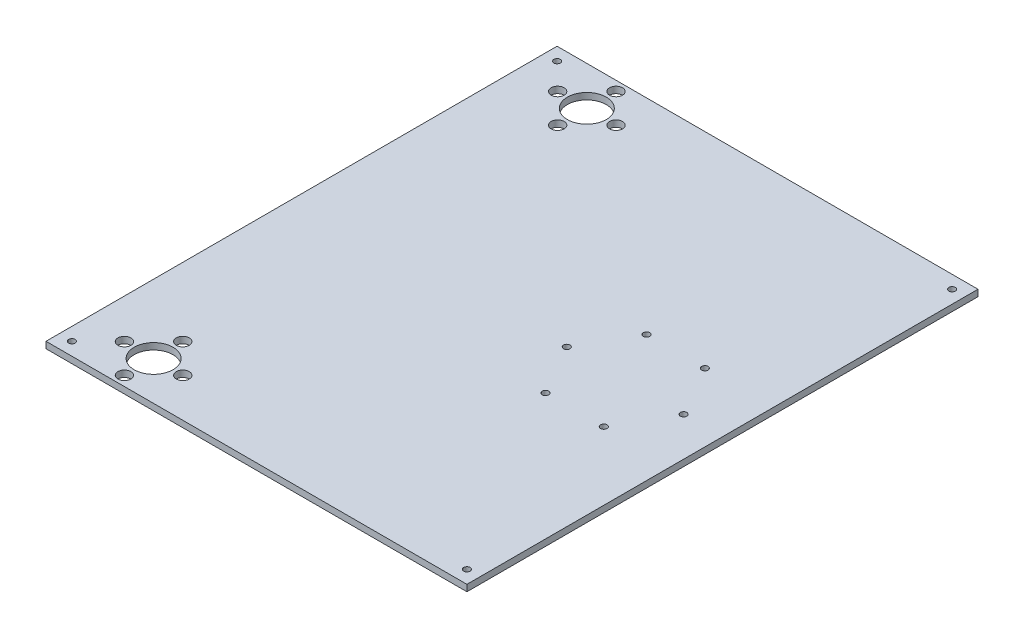
SolidWorks part; units mm, degrees
ref_plane "Front Plane" through (0, 0, 0) normal (0, 0, 1) x (1, 0, 0)
ref_plane "Top Plane" through (0, 0, 0) normal (0, 1, 0) x (1, 0, 0)
ref_plane "Right Plane" through (0, 0, 0) normal (1, 0, 0) x (0, 0, -1)
sketch "Sketch1" plane through (0, 0, 0) normal (0, 1, 0) x (1, 0, 0)
  line L1 (-162.25, 197) -> (162.25, 197)
  line L2 (-162.25, 197) -> (-162.25, -197)
  line L3 (-162.25, -197) -> (162.25, -197)
  line L4 (162.25, 197) -> (162.25, -197)
  line L5 (-162.25, 197) -> (162.25, -197) construction
  line L6 (-162.25, -197) -> (162.25, 197) construction
  point P0 (0, 0)
  dimension "D1" = 394
  dimension "D2" = 324.5
extrude "Boss-Extrude1" add sketch "Sketch1" along normal blind 5
sketch "Sketch2" plane through (0, 5, 0) normal (0, 1, 0) x (1, 0, 0)
  line L0 (162.25, 197) -> (-162.25, 197) construction
  line L1 (162.25, -197) -> (162.25, 197) construction
  line L2 (-162.25, 197) -> (-162.25, -197) construction
  line L3 (-162.25, -197) -> (162.25, -197) construction
  circle A0 centre (152.25, 187) radius 2.5
  circle A1 centre (-152.25, 187) radius 2.5
  circle A2 centre (-152.25, -187) radius 2.5
  circle A3 centre (152.25, -187) radius 2.5
  dimension "D1" = 5
  dimension "D4" = 5
  dimension "D9" = 5
  dimension "D10" = 5
  dimension "D2" = 10
  dimension "D3" = 10
  dimension "D5" = 10
  dimension "D6" = 10
  dimension "D7" = 10
  dimension "D8" = 10
  dimension "D11" = 10
  dimension "D12" = 10
extrude "Cut-Extrude1" cut sketch "Sketch2" against normal through all
sketch "Sketch3" plane through (0, 5, 0) normal (0, 1, 0) x (1, 0, 0)
  line L1 (37.25, 0) -> (137.25, 0) construction
  line L2 (162.25, -197) -> (162.25, 197) construction
  circle A0 centre (132.25, 0) radius 2.5
  circle A3 centre (109.75, -38.9711) radius 2.5
  circle A4 centre (64.75, -38.9711) radius 2.5
  circle A5 centre (42.25, 0) radius 2.5
  circle A6 centre (64.75, 38.9711) radius 2.5
  circle A7 centre (109.75, 38.9711) radius 2.5
  point P21 (87.25, 0)
  dimension "D1" = 5
  dimension "D4" = 100
  dimension "D2" = 25
  dimension "D6" = 6
extrude "Cut-Extrude2" cut sketch "Sketch3" against normal blind 5
sketch "Sketch4" plane through (0, 5, 0) normal (0, 1, 0) x (1, 0, 0)
  line L0 (162.25, 197) -> (-162.25, 197) construction
  line L1 (162.25, -197) -> (162.25, 197) construction
  line L2 (-162.25, -197) -> (162.25, -197) construction
  circle A0 centre (-109.31, 167) radius 15
  circle A1 centre (-109.31, -167) radius 15
  circle A2 centre (-109.31, 189.5) radius 5
  circle A6 centre (-109.31, -189.5) radius 5
  circle A16 centre (-131.81, -167) radius 5
  circle A17 centre (-109.31, -144.5) radius 5
  circle A18 centre (-86.81, -167) radius 5
  circle A19 centre (-86.81, 167) radius 5
  circle A20 centre (-109.31, 144.5) radius 5
  circle A21 centre (-131.81, 167) radius 5
  point P21 (-85.25, 167)
  point P24 (-96.215, -167)
  point P25 (-109.31, -167)
  point P30 (-85.25, -167)
  point P32 (-96.215, 167)
  point P34 (-109.31, 167)
  dimension "D1" = 30
  dimension "D4" = 30
  dimension "D7" = 10
  dimension "D10" = 10
  dimension "D2" = 30
  dimension "D3" = 271.56
  dimension "D5" = 30
  dimension "D6" = 271.56
  dimension "D8" = 22.5
  dimension "D11" = 22.5
  dimension "D9" = 4
  dimension "D12" = 4
extrude "Cut-Extrude4" cut sketch "Sketch4" against normal through all
